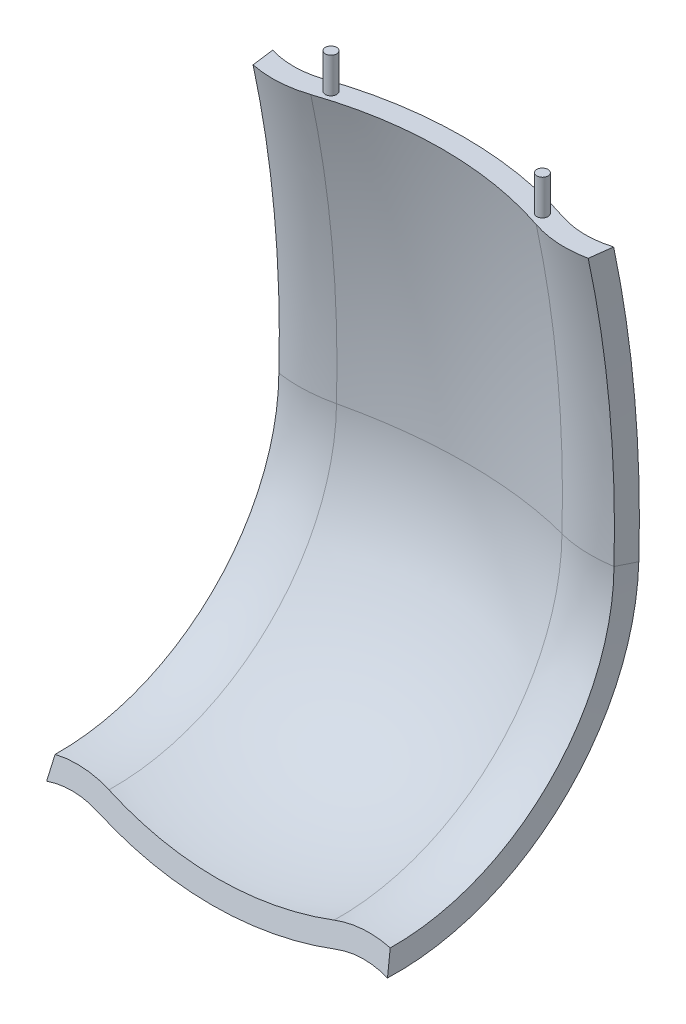
SolidWorks part; units mm, degrees
material "Rubber"
ref_plane "Front Plane" through (0, 0, 0) normal (0, 0, 1) x (1, 0, 0)
ref_plane "Top Plane" through (0, 0, 0) normal (0, 1, 0) x (1, 0, 0)
ref_plane "Right Plane" through (0, 0, 0) normal (1, 0, 0) x (0, 0, -1)
sketch "Sketch2" plane through (0, 0, 0) normal (0, 1, 0) x (1, 0, 0)
  line L0 (106.1717, 4.7871) -> (104.1354, -11.2142)
  line L1 (-133.5425, -11.2302) -> (-135.5913, 4.7676)
  arc A0 (-94.8063, -9.0192) -> (65.0033, -8.9115) centre (-14.7419, -245.8431) cw
  arc A1 (-99.5929, 5.2028) -> (69.7901, 5.3105) centre (-14.7419, -245.8431) cw
  arc A2 (-99.5929, 5.2028) -> (-135.5913, 4.7676) centre (-118.2787, 61.7816) cw
  arc A3 (-94.8063, -9.0192) -> (-133.5425, -11.2302) centre (-118.2787, 61.7816) cw
  arc A4 (69.7901, 5.3105) -> (106.1717, 4.7871) centre (88.7971, 61.7824) ccw
  arc A5 (65.0033, -8.9115) -> (104.1354, -11.2142) centre (88.7971, 61.7824) ccw
sketch "Sketch3" plane through (0, 0, 0) normal (1, 0, 0) x (0, 0, -1)
  line L1 (-148.8135, -197.4777) -> (-156.4904, -372.3093) construction
  line L2 (8.3536, 0) -> (26.0956, -203.1171) construction
  arc A0 (-156.4904, -372.3093) -> (26.0956, -203.1171) centre (-148.8135, -197.4777) ccw
  arc A2 (26.0956, -203.1171) -> (8.3536, 0) centre (-829.6053, -175.528) ccw
sweep "Sweep1" add profiles "Sketch2" path "Sketch3"
sketch "Sketch4" plane through (0, 0, 0) normal (0, 1, 0) x (1, 0, 0)
  circle A0 centre (-89.6435, 0.1407) radius 4
  circle A1 centre (60.3051, 0.1412) radius 4
  dimension "D1" = 8
extrude "Boss-Extrude1" add sketch "Sketch4" along normal blind 25
